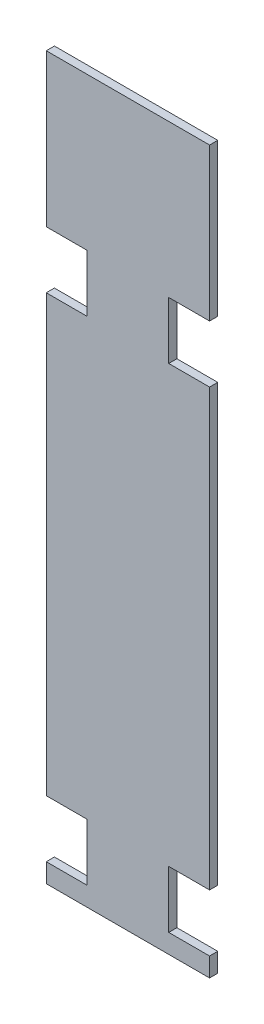
SolidWorks part; units mm, degrees
material "Thornel VCB-20 碳布"
ref_plane "前视基准面" through (0, 0, 0) normal (0, 0, 1) x (1, 0, 0)
ref_plane "上视基准面" through (0, 0, 0) normal (0, 1, 0) x (1, 0, 0)
ref_plane "右视基准面" through (0, 0, 0) normal (1, 0, 0) x (0, 0, -1)
other "Configuration Table"
sketch "草图1" plane through (0, 0, 0) normal (0, 0, 1) x (1, 0, 0)
  line L0 (0, 240) -> (0, 265)
  line L1 (0, 0) -> (60, 0)
  line L2 (0, 0) -> (0, 240)
  line L3 (0, 240) -> (60, 240) construction
  line L4 (60, 0) -> (60, 240)
  line L5 (0, 265) -> (60, 265)
  line L6 (60, 265) -> (60, 240)
  dimension "D1" = 60
  dimension "D2" = 240
  dimension "D3" = 25
extrude "凸台-拉伸1" add sketch "草图1" along normal blind 3
sketch "草图4" plane through (0, 0, 0) normal (0, 0, -1) x (-1, 0, 0)
  line L0 (-60, 7) -> (-45, 7)
  line L1 (-60, 0) -> (-60, 265) construction
  line L2 (-45, 7) -> (-45, 28)
  line L3 (-45, 28) -> (-60, 28)
  line L4 (0, 0) -> (-60, 0) construction
  line L5 (-60, 28) -> (-60, 7)
  line L6 (0, 265) -> (0, 0) construction
  line L7 (0, 28) -> (-15, 28)
  line L8 (0, 28) -> (0, 7)
  line L9 (0, 7) -> (-15, 7)
  line L10 (-15, 28) -> (-15, 7)
  line L11 (-60, 216) -> (0, 216) construction
  line L13 (0, 209) -> (-15, 209)
  line L14 (-15, 209) -> (-15, 188)
  line L15 (-15, 188) -> (0, 188)
  line L16 (-60, 209) -> (-45, 209)
  line L17 (-45, 209) -> (-45, 188)
  line L18 (-45, 188) -> (-60, 188)
  line L19 (-60, 188) -> (-60, 209)
  line L20 (0, 209) -> (0, 188)
  line L21 (-30, 0) -> (-30, 216) construction
  line L25 (-60, 265) -> (0, 265) construction
  dimension "D1" = 7
  dimension "D2" = 21
  dimension "D3" = 15
  dimension "D4" = 49
  dimension "D5" = 21
  dimension "D6" = 7
extrude "切除-拉伸1" cut sketch "草图4" against normal blind 3
